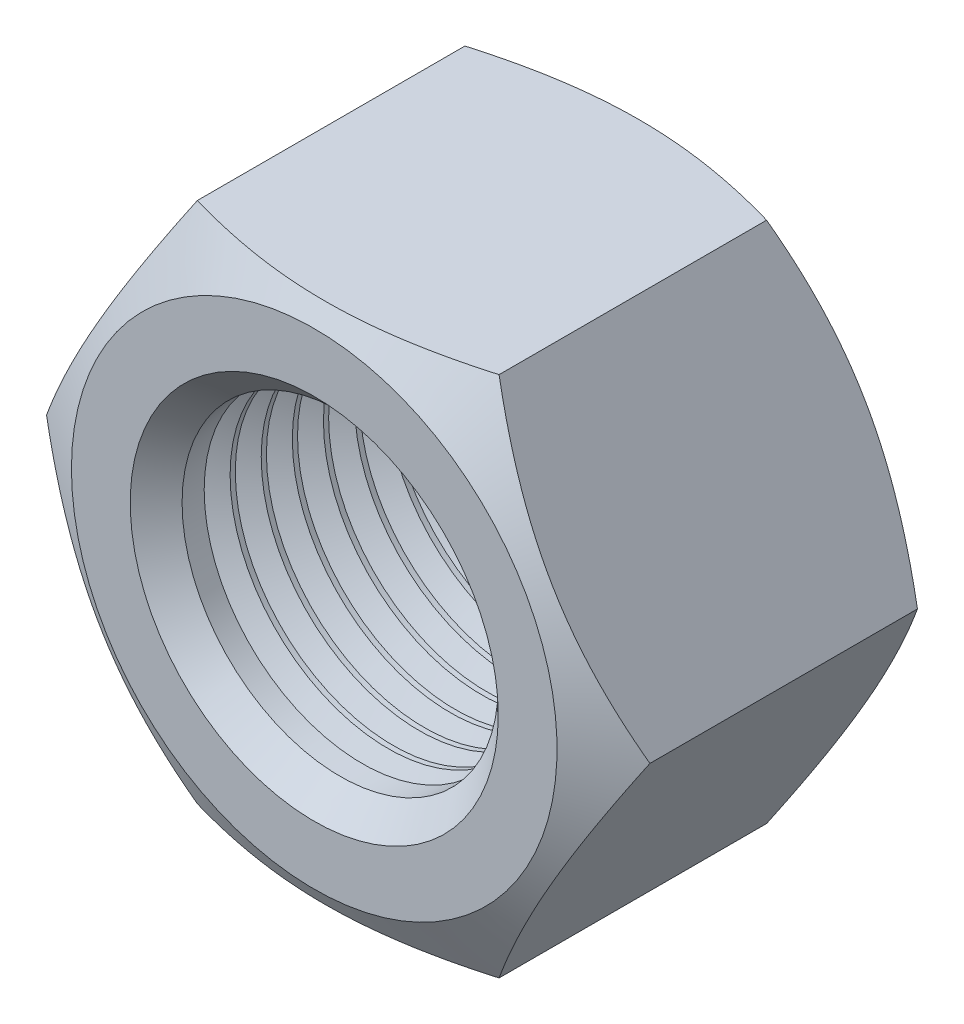
SolidWorks part; units mm, degrees
ref_plane "Front" through (0, 0, 0) normal (0, 0, 1) x (1, 0, 0)
ref_plane "Top" through (0, 0, 0) normal (0, 1, 0) x (1, 0, 0)
ref_plane "Right" through (0, 0, 0) normal (1, 0, 0) x (0, 0, -1)
other "Configuration Table"
sketch "Sketch1" plane through (0, 0, 0) normal (0, 0, 1) x (1, 0, 0)
  line L1 (13.2791, -23) -> (26.5581, 0)
  line L2 (26.5581, 0) -> (13.2791, 23)
  line L3 (13.2791, 23) -> (-13.2791, 23)
  line L4 (-13.2791, 23) -> (-26.5581, 0)
  line L5 (-26.5581, 0) -> (-13.2791, -23)
  line L6 (-13.2791, -23) -> (13.2791, -23)
  circle A0 centre (0, 0) radius 23 construction
  circle A1 centre (0, 0) radius 13.9175
extrude "BaseNut" add sketch "Sketch1" against normal blind 28.6
cosmetic thread "ThreadCosmetic1" [suppressed] parameters "D2"=32.4
sketch "Sketch2" plane through (15.0481, 0, -16.7061) normal (0, 1, 0) x (0, 0, -1)
  line L0 (-23.7227, 15.0481) -> (22.0646, 15.0481) construction
  line L2 (11.8939, 41.6062) -> (11.8939, 28.3272) construction
  line L4 (11.8939, 41.6062) -> (-16.7061, 41.6062) construction
  line L8 (9.8396, 41.6062) -> (11.8939, 38.0481)
  line L9 (11.8939, 41.6062) -> (9.8396, 41.6062)
  line L10 (11.8939, 38.0481) -> (11.8939, 41.6062)
  dimension "D1" = 30
revolve "Chamfer1" cut sketch "Sketch2" angle 360 about L0
sketch "Sketch6" plane through (-9.1975, 0, -10.2525) normal (0, 1, 0) x (0, 0, 1)
  line L0 (23.3574, 9.1975) -> (-22.3023, 9.1975) construction
  line L2 (-18.3475, 23.115) -> (-18.3475, 25.3975)
  line L4 (-18.3475, 25.3975) -> (-17.0297, 23.115)
  line L6 (-17.0297, 23.115) -> (-18.3475, 23.115)
  dimension "D2" = 60
revolve "EndChamfer1" cut sketch "Sketch6" angle 360 about L0
sketch "Sketch5" plane through (-14.793, 0, -16.9612) normal (0, 1, 0) x (0, 0, 1)
  line L0 (-22.5748, 14.793) -> (24.743, 14.793) construction
  line L2 (16.9612, 36.168) -> (16.9612, 41.3511)
  line L4 (16.9612, 41.3511) -> (13.9688, 41.3511)
  line L6 (13.9688, 41.3511) -> (16.9612, 36.168)
  dimension "dw1" = 42.75
  dimension "D2" = 30
revolve "Chamfer2" cut sketch "Sketch5" angle 360 about L0
sketch "Sketch3" plane through (-20.9491, 1.8856, 0) normal (0, 0, 1) x (1, 0, 0)
  circle A1 centre (20.9491, -1.8856) radius 13.9175 construction
  circle A2 centre (20.9491, -1.8856) radius 21.375
  circle A3 centre (20.9491, -1.8856) radius 13.9175
  dimension "dw" = 42.75
extrude "Extrude1" [suppressed] add sketch "Sketch3" along normal blind 0.8
chamfer "EndChamfer3" [suppressed] distance 0.9533 angle 45
chamfer "EndChamfer2" distance 2.2825 angle 45 1 edges at (13.9175, 0, 0)
sketch "Sketch7" plane through (0, 0, 0) normal (0, 1, 0) x (1, 0, 0)
  line L0 (0, 48.6183) -> (0, -13.0076) construction
  line L1 (11.635, 28.4234) -> (13.9175, 28.4234)
  line L2 (13.9175, 28.4234) -> (15.8942, 27.2822)
  line L3 (15.8942, 27.2822) -> (13.9175, 26.1409)
  line L4 (13.9175, 26.1409) -> (11.635, 26.1409)
  line L5 (11.635, 26.1409) -> (11.635, 28.4234)
  line L6 (13.9175, 27.2822) -> (-13.9175, 27.2822) construction
revolve "Cut-Revolve10" cut sketch "Sketch7" angle 360 about L0
pattern_linear "LPattern10" count 9 spacing 2.739 along (0, 0, 1) of "Cut-Revolve10"
equation "\"D1@EndChamfer3\" = \"m@BaseNut\" / 30"
equation "\"s1@Sketch2\" = \"s@Sketch1\""
equation "\"D2@Sketch7\" = \"D1@Sketch1\""
equation "\"D1@Sketch7\" = (  \"D2@ThreadCosmetic1\" - \"D1@Sketch1\" )  / 2"
equation "\"D3@LPattern10\" = \"D1@Sketch7\" * 1.2"
equation "\"D1@LPattern10\" = \"m@BaseNut\" / \"D3@LPattern10\" - 1"
equation "\"D1@EndChamfer2\" = (  \"da@Sketch6\" - \"D1@Sketch1\" )  / 2"
